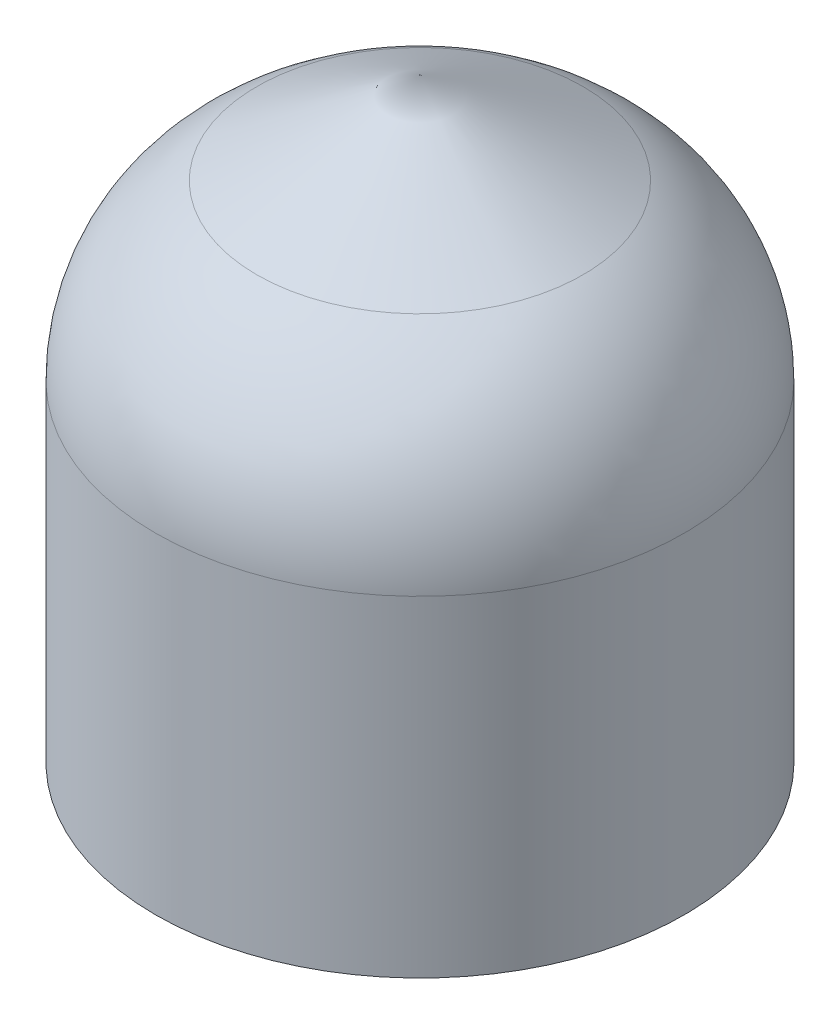
SolidWorks part; units mm, degrees
ref_plane "Alzado" through (0, 0, 0) normal (0, 0, 1) x (1, 0, 0)
ref_plane "Planta" through (0, 0, 0) normal (0, 1, 0) x (1, 0, 0)
ref_plane "Vista lateral" through (0, 0, 0) normal (1, 0, 0) x (0, 0, -1)
sketch "Croquis2" plane through (0, 0, 0) normal (0, 0, 1) x (1, 0, 0)
  line L0 (0, 5.6618) -> (0, 0) construction
  line L1 (-2.5, 0) -> (-4, 0)
  line L2 (-4, 0) -> (-4, 5)
  line L3 (-2.4671, 7.6168) -> (0, 9)
  line L4 (0, 9) -> (0, 7)
  line L5 (0, 7) -> (-2.5, 7)
  line L6 (-2.5, 7) -> (-2.5, 0)
  line L7 (0, 0) -> (-4.686, 0) construction
  arc A0 (-4, 5) -> (-2.4671, 7.6168) centre (-1, 5) cw
  dimension "D5" = 3
  dimension "D1" = 5
  dimension "D2" = 8
  dimension "D3" = 7
  dimension "D4" = 9
  dimension "D6" = 5
revolve "Revolución1" add sketch "Croquis2" angle 360 about L0
